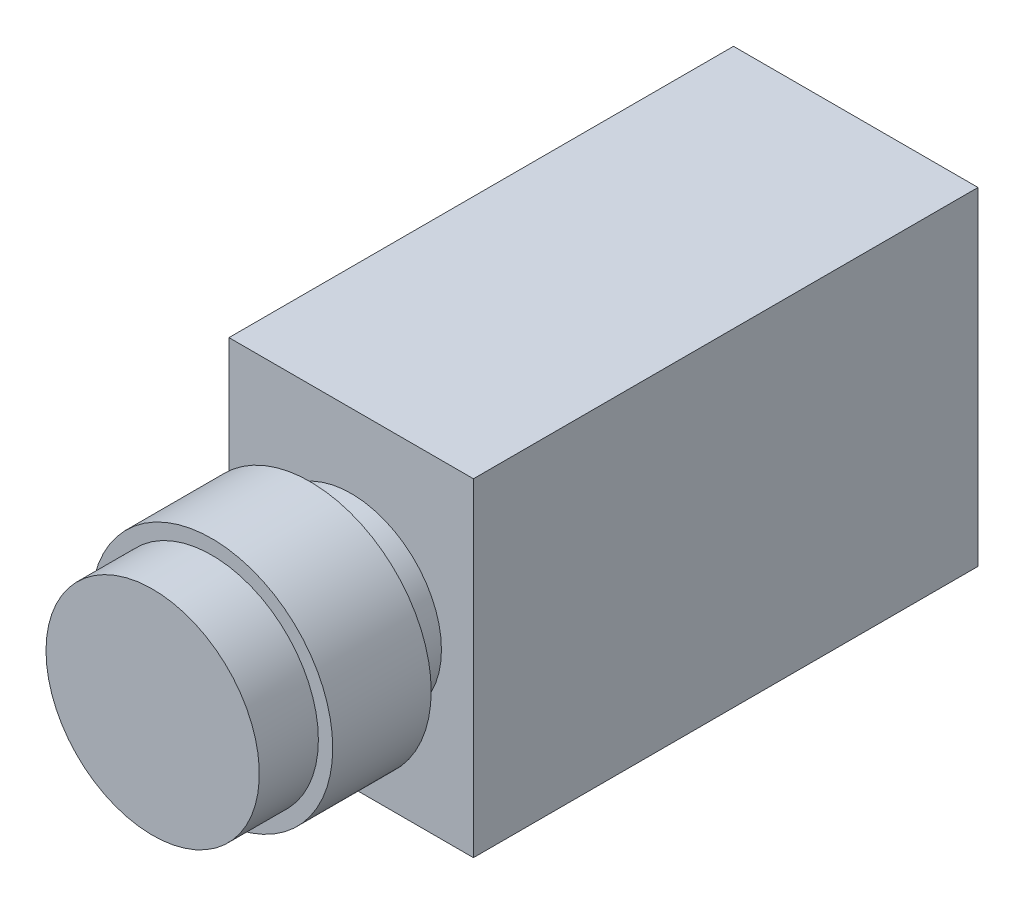
SolidWorks part; units mm, degrees
ref_plane "Front Plane" through (0, 0, 0) normal (0, 0, 1) x (1, 0, 0)
ref_plane "Top Plane" through (0, 0, 0) normal (0, 1, 0) x (1, 0, 0)
ref_plane "Right Plane" through (0, 0, 0) normal (1, 0, 0) x (0, 0, -1)
sketch "Sketch1" plane through (0, 0, 0) normal (0, 0, 1) x (1, 0, 0)
  circle A0 centre (0, 0) radius 14.75
  dimension "D1" = 29.5
extrude "Boss-Extrude1" add sketch "Sketch1" along normal blind 12
sketch "Sketch2" plane through (0, 0, 0) normal (0, 0, -1) x (-1, 0, 0)
  circle A0 centre (0, 0) radius 13
  dimension "D1" = 26
extrude "Boss-Extrude2" add sketch "Sketch2" against normal blind 19.2
sketch "Sketch4" plane through (0, 0, 0) normal (0, 0, -1) x (-1, 0, 0)
  circle A0 centre (0, 0) radius 11
  dimension "D1" = 22
extrude "Boss-Extrude4" add sketch "Sketch4" along normal blind 61.5
sketch "Sketch3" plane through (0, 0, 0) normal (0, 0, -1) x (-1, 0, 0)
  line L1 (-14.9, 20) -> (14.9, 20)
  line L2 (-14.9, 20) -> (-14.9, -20)
  line L3 (-14.9, -20) -> (14.9, -20)
  line L4 (14.9, 20) -> (14.9, -20)
  line L5 (-14.9, 20) -> (14.9, -20) construction
  line L6 (-14.9, -20) -> (14.9, 20) construction
  point P0 (0, 0)
  dimension "D1" = 40
  dimension "D2" = 29.8
extrude "Boss-Extrude3" add sketch "Sketch3" along normal blind 61.5 from offset 5 separate body
